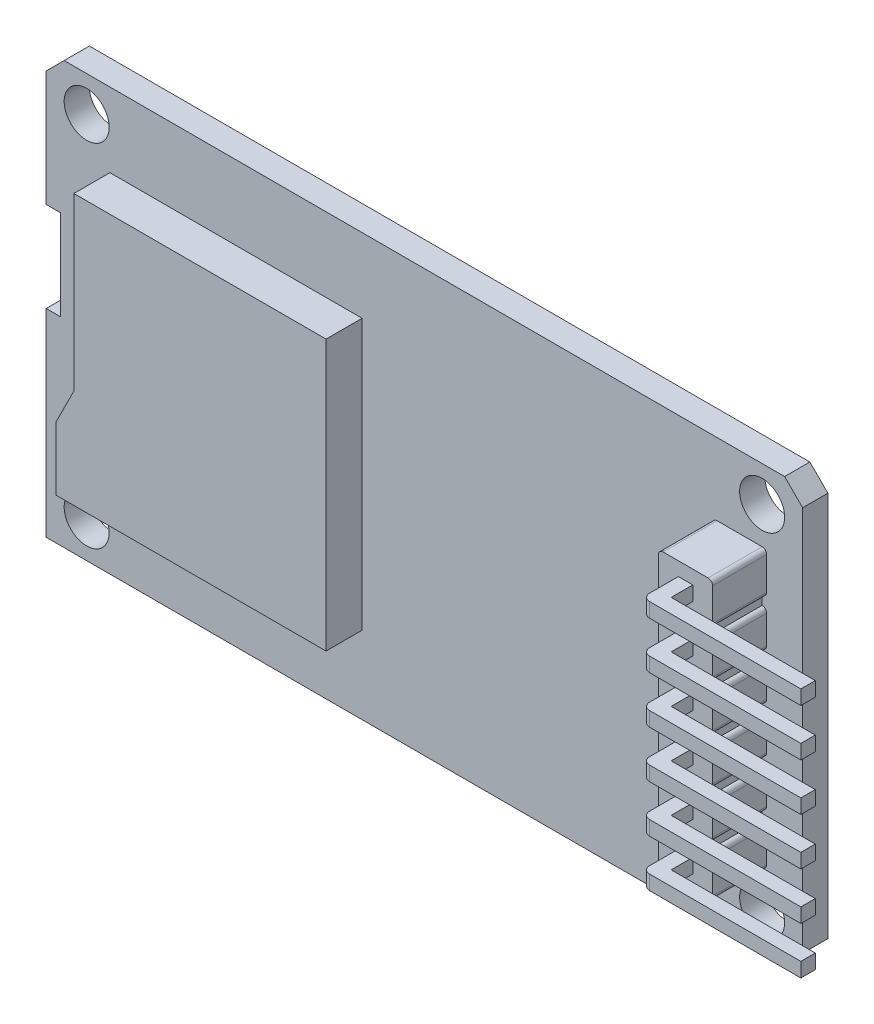
SolidWorks part; units mm, degrees
ref_plane "Front Plane" through (0, 0, 0) normal (0, 0, 1) x (1, 0, 0)
ref_plane "Top Plane" through (0, 0, 0) normal (0, 1, 0) x (1, 0, 0)
ref_plane "Right Plane" through (0, 0, 0) normal (1, 0, 0) x (0, 0, -1)
sketch "Sketch1" plane through (0, 0, 0) normal (0, 0, 1) x (1, 0, 0)
  line L0 (-17.6235, 11.42) -> (-16.6235, 12.42)
  line L1 (-17.6235, -11) -> (23.3765, -11)
  line L3 (-16.6235, 12.42) -> (23.3765, 12.42)
  line L4 (24.3765, -10) -> (24.3765, 11.42)
  line L5 (23.3765, 12.42) -> (24.3765, 11.42)
  line L6 (23.3765, -11) -> (24.3765, -10)
  line L7 (-17.6235, 0) -> (-16.8235, 0)
  line L8 (-16.8235, 0) -> (-16.8235, 5)
  line L9 (-16.8235, 5) -> (-17.6235, 5)
  line L10 (-17.6235, 5) -> (-17.6235, 11.42)
  line L11 (-17.6235, 0) -> (-17.6235, -11)
  point P1 (24.3765, 12.42)
  point P2 (-17.6235, 12.42)
  point P3 (24.3765, -11)
  dimension "D1" = 42
  dimension "D2" = 23.42
  dimension "D3" = 11
  dimension "D4" = 5
  dimension "D8" = 0.8
extrude "Boss-Extrude1" add sketch "Sketch1" along normal blind 1.4 contours L0 L3 L5 L4 L6 L1 L11 L7 L8 L9 L10
hole_wizard "Ø2.5 (2.5) Diameter Slot1" positions "Sketch4" profile "Sketch5" size "Ø2.5" standard "ISO" slot yes end condition through all
sketch "Sketch4" plane through (0, 0, 1.4) normal (0, 0, 1) x (1, 0, 0)
  line L2 (-15.3735, 10.46) -> (-15.3735, 12.42) construction
  line L3 (-16.6235, 12.42) -> (23.3765, 12.42) construction
  line L5 (-15.3735, -9.04) -> (-15.3735, -11) construction
  line L6 (-17.6235, -11) -> (23.3765, -11) construction
  line L13 (22.1265, 10.46) -> (-15.3735, 10.46) construction
  line L15 (22.1265, 10.46) -> (22.1265, -9.04) construction
  line L17 (-15.3735, -9.04) -> (22.1265, -9.04) construction
  line L19 (-15.3735, 10.46) -> (-15.3735, -9.04) construction
  line L21 (-15.3735, -9.04) -> (-17.6235, -9.04) construction
  line L22 (-17.6235, 0) -> (-17.6235, -11) construction
  line L24 (22.1265, 10.46) -> (24.3765, 10.46) construction
  line L25 (24.3765, -10) -> (24.3765, 11.42) construction
  point P0 (-15.3735, -9.04)
  point P2 (-15.3735, 10.46)
  point P4 (22.1265, -9.04)
  point P6 (22.1265, 10.46)
  dimension "D1" = 19.5
  dimension "D2" = 37.5
sketch "Sketch5" plane through (-15.3735, -9.04, 1.4) normal (1, 0, 0) x (0, -1, 0)
  line L0 (0, 0) -> (0, 1.4)
  line L1 (0, 1.4) -> (1.25, 1.4)
  line L2 (1.25, 1.4) -> (1.25, 0)
  line L5 (1.25, 0) -> (0, 0)
  line L11 (0, -6.35) -> (0, 15.6736) construction
  dimension "Thru Hole Dia." = 2.5
  dimension "Thru Hole Depth" = 1.4
sketch "Sketch6" plane through (0, 0, 1.4) normal (0, 0, 1) x (1, 0, 0)
  line L0 (-15.0835, -6.7) -> (-0.0835, -6.7)
  line L1 (-17.6235, -11) -> (23.3765, -11) construction
  line L2 (-17.6235, 0) -> (-17.6235, -11) construction
  line L3 (-0.0835, -6.7) -> (-0.0835, 8.3)
  line L4 (-0.0835, 8.3) -> (-14.0835, 8.3)
  line L5 (-14.0835, 8.3) -> (-14.0835, -1.2)
  line L6 (-14.0835, -1.2) -> (-15.0835, -3.2)
  line L7 (-15.0835, -3.2) -> (-15.0835, -6.7)
  dimension "D1" = 4.3
  dimension "D2" = 15
  dimension "D3" = 2.54
  dimension "D4" = 15
  dimension "D5" = 14
  dimension "D6" = 3.5
  dimension "D7" = 9.5
extrude "Boss-Extrude2" add sketch "Sketch6" along normal blind 2
sketch "Sketch7" plane through (0, 0, 1.4) normal (0, 0, 1) x (1, 0, 0)
  line L0 (22.1265, 6.1) -> (22.1265, 5.6)
  line L1 (22.1265, 8.42) -> (19.6265, 8.42)
  line L2 (19.6265, 6.1) -> (19.6265, 5.6)
  line L3 (22.1265, -7) -> (19.6265, -7)
  line L4 (19.6265, 3.53) -> (19.6265, 3.03)
  line L5 (-17.6235, -11) -> (23.3765, -11) construction
  line L6 (22.3765, 8.17) -> (22.3765, 6.35)
  line L7 (19.3765, 8.17) -> (19.3765, 6.35)
  line L8 (19.3765, 5.35) -> (19.3765, 3.78)
  line L9 (22.3765, 5.35) -> (22.3765, 3.78)
  line L10 (22.3765, 2.78) -> (22.3765, 1.21)
  line L11 (22.1265, -1.61) -> (22.1265, -2.11)
  line L12 (19.6265, -1.61) -> (19.6265, -2.11)
  line L13 (22.1265, -4.18) -> (22.1265, -4.68)
  line L14 (19.6265, -4.68) -> (19.6265, -4.18)
  line L21 (19.3765, 2.78) -> (19.3765, 1.21)
  line L22 (19.3765, 0.21) -> (19.3765, -1.36)
  line L23 (22.3765, 0.21) -> (22.3765, -1.36)
  line L24 (22.3765, -2.36) -> (22.3765, -3.93)
  line L25 (19.3765, -2.36) -> (19.3765, -3.93)
  line L26 (19.3765, -4.93) -> (19.3765, -6.75)
  line L27 (22.3765, -4.93) -> (22.3765, -6.75)
  line L28 (22.1265, 3.53) -> (22.1265, 3.03)
  line L29 (22.1265, 0.96) -> (22.1265, 0.46)
  line L30 (19.6265, 0.96) -> (19.6265, 0.46)
  arc A0 (22.3765, -6.75) -> (22.1265, -7) centre (22.1265, -6.75) cw
  arc A1 (19.6265, -7) -> (19.3765, -6.75) centre (19.6265, -6.75) cw
  arc A2 (19.6265, -4.68) -> (19.3765, -4.93) centre (19.6265, -4.93) ccw
  arc A3 (22.1265, -4.68) -> (22.3765, -4.93) centre (22.1265, -4.93) cw
  arc A4 (19.6265, -4.18) -> (19.3765, -3.93) centre (19.6265, -3.93) cw
  arc A5 (22.1265, -4.18) -> (22.3765, -3.93) centre (22.1265, -3.93) ccw
  arc A6 (22.1265, -2.11) -> (22.3765, -2.36) centre (22.1265, -2.36) cw
  arc A7 (19.6265, -2.11) -> (19.3765, -2.36) centre (19.6265, -2.36) ccw
  arc A8 (19.6265, -1.61) -> (19.3765, -1.36) centre (19.6265, -1.36) cw
  arc A9 (22.1265, -1.61) -> (22.3765, -1.36) centre (22.1265, -1.36) ccw
  arc A10 (22.1265, 0.46) -> (22.3765, 0.21) centre (22.1265, 0.21) cw
  arc A11 (19.6265, 0.46) -> (19.3765, 0.21) centre (19.6265, 0.21) ccw
  arc A12 (19.6265, 0.96) -> (19.3765, 1.21) centre (19.6265, 1.21) cw
  arc A13 (22.1265, 0.96) -> (22.3765, 1.21) centre (22.1265, 1.21) ccw
  arc A14 (19.6265, 3.03) -> (19.3765, 2.78) centre (19.6265, 2.78) ccw
  arc A15 (22.1265, 3.03) -> (22.3765, 2.78) centre (22.1265, 2.78) cw
  arc A16 (22.1265, 3.53) -> (22.3765, 3.78) centre (22.1265, 3.78) ccw
  arc A17 (19.6265, 3.53) -> (19.3765, 3.78) centre (19.6265, 3.78) cw
  arc A18 (19.3765, 5.35) -> (19.6265, 5.6) centre (19.6265, 5.35) cw
  arc A19 (22.1265, 5.6) -> (22.3765, 5.35) centre (22.1265, 5.35) cw
  arc A20 (22.1265, 6.1) -> (22.3765, 6.35) centre (22.1265, 6.35) ccw
  arc A21 (19.6265, 6.1) -> (19.3765, 6.35) centre (19.6265, 6.35) cw
  arc A22 (19.6265, 8.42) -> (19.3765, 8.17) centre (19.6265, 8.17) ccw
  arc A23 (22.1265, 8.42) -> (22.3765, 8.17) centre (22.1265, 8.17) cw
  point P11 (19.3765, -7)
  point P73 (19.3765, 8.42)
  point P76 (22.3765, 8.42)
  dimension "D1" = 0.25
  dimension "D2" = 3
  dimension "D3" = 15.42
  dimension "D4" = 4
extrude "Boss-Extrude3" add sketch "Sketch7" along normal blind 3
sketch "Sketch8" plane through (0, 0, 4.4) normal (0, 0, 1) x (1, 0, 0)
  line L1 (20.4765, -5.44) -> (21.2765, -5.44)
  line L2 (20.4765, -5.44) -> (20.4765, -6.24)
  line L3 (20.4765, -6.24) -> (21.2765, -6.24)
  line L4 (21.2765, -5.44) -> (21.2765, -6.24)
  line L5 (20.4765, -5.44) -> (21.2765, -6.24) construction
  line L6 (20.4765, -6.24) -> (21.2765, -5.44) construction
  line L8 (21.2765, -2.82) -> (21.2765, -3.62)
  line L9 (20.4765, -2.82) -> (21.2765, -2.82)
  line L10 (20.4765, -2.82) -> (20.4765, -3.62)
  line L11 (20.4765, -3.62) -> (21.2765, -3.62)
  line L12 (21.2765, -0.2) -> (21.2765, -1)
  line L13 (20.4765, -0.2) -> (21.2765, -0.2)
  line L14 (20.4765, -0.2) -> (20.4765, -1)
  line L15 (20.4765, -1) -> (21.2765, -1)
  line L16 (21.2765, 2.42) -> (21.2765, 1.62)
  line L17 (20.4765, 2.42) -> (21.2765, 2.42)
  line L18 (20.4765, 2.42) -> (20.4765, 1.62)
  line L19 (20.4765, 1.62) -> (21.2765, 1.62)
  line L20 (21.2765, 5.04) -> (21.2765, 4.24)
  line L21 (20.4765, 5.04) -> (21.2765, 5.04)
  line L22 (20.4765, 5.04) -> (20.4765, 4.24)
  line L23 (20.4765, 4.24) -> (21.2765, 4.24)
  line L24 (21.2765, 7.66) -> (21.2765, 6.86)
  line L25 (20.4765, 7.66) -> (21.2765, 7.66)
  line L26 (20.4765, 7.66) -> (20.4765, 6.86)
  line L27 (20.4765, 6.86) -> (21.2765, 6.86)
  point P0 (20.8765, -5.84)
  dimension "D1" = 0.8
  dimension "D2" = 0.8
  dimension "D3" = 6
extrude "Boss-Extrude4" add sketch "Sketch8" along normal blind 2
sketch "Sketch9" plane through (21.2765, 0, 0) normal (1, 0, 0) x (0, 0, -1)
  line L0 (-6.4, 7.66) -> (-6.4, 6.86)
  line L1 (-6.4, 7.66) -> (-5.6, 7.66)
  line L2 (-6.4, 6.86) -> (-5.6, 6.86)
  line L3 (-5.6, 7.66) -> (-5.6, 6.86)
  dimension "D1" = 0.8
extrude "Boss-Extrude5" add sketch "Sketch9" along normal blind 8
pattern_linear "LPattern1" count 6 spacing 2.62 along (0, -1, 0) of "Boss-Extrude5"
fillet "Fillet1" radius 0.4 6 edges at (20.4765, 7.26, 6.4) (20.4765, 4.64, 6.4) (20.4765, 2.02, 6.4) (20.4765, -0.6, 6.4) (20.4765, -3.22, 6.4) (20.4765, -5.84, 6.4)
